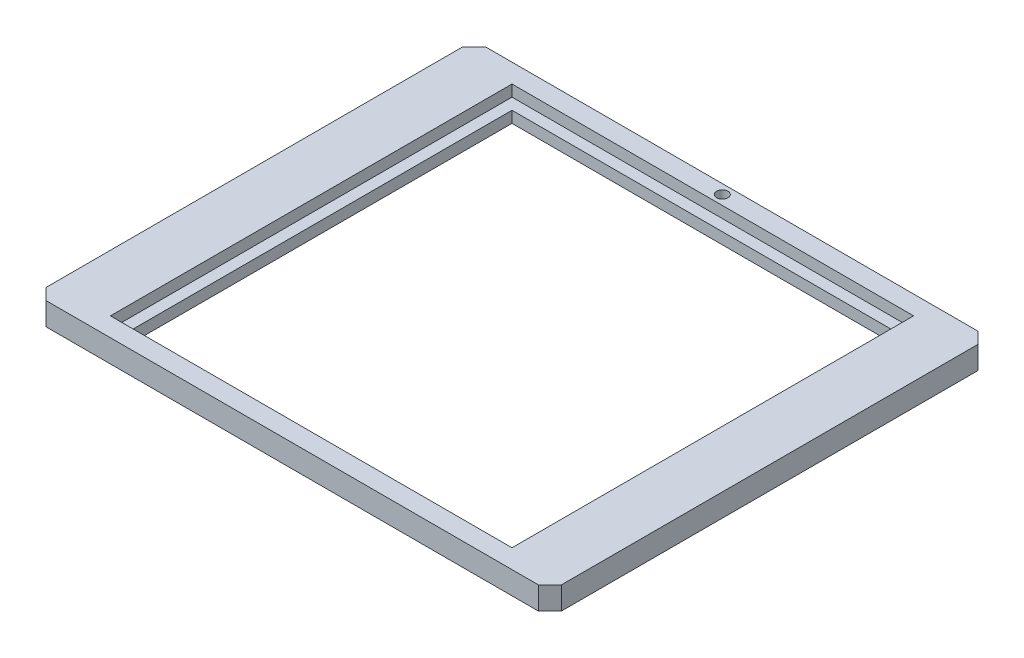
SolidWorks part; units mm, degrees
ref_plane "정면" through (0, 0, 0) normal (0, 0, 1) x (1, 0, 0)
ref_plane "윗면" through (0, 0, 0) normal (0, 1, 0) x (1, 0, 0)
ref_plane "우측면" through (0, 0, 0) normal (1, 0, 0) x (0, 0, -1)
sketch "스케치3" plane through (0, 0, 0) normal (0, 1, 0) x (1, 0, 0)
  line L1 (-68, -58) -> (68, -58)
  line L2 (-68, -58) -> (-68, 58)
  line L3 (-68, 58) -> (68, 58)
  line L4 (68, -58) -> (68, 58)
  line L5 (-68, -58) -> (68, 58) construction
  line L6 (-68, 58) -> (68, -58) construction
  point P0 (0, 0)
  dimension "D1" = 136
  dimension "D2" = 116
extrude "보스-돌출2" add sketch "스케치3" along normal blind 6
sketch "스케치4" plane through (0, 6, 0) normal (0, 1, 0) x (1, 0, 0)
  line L1 (-53, -53) -> (53, -53)
  line L2 (-53, -53) -> (-53, 53)
  line L3 (-53, 53) -> (53, 53)
  line L4 (53, -53) -> (53, 53)
  line L5 (-53, -53) -> (53, 53) construction
  line L6 (-53, 53) -> (53, -53) construction
  point P0 (0, 0)
  dimension "D1" = 106
  dimension "D2" = 106
extrude "컷-돌출1" cut sketch "스케치4" against normal blind 3
sketch "스케치5" plane through (0, 3, 0) normal (0, 1, 0) x (1, 0, 0)
  line L1 (-50, -50) -> (50, -50)
  line L2 (-50, -50) -> (-50, 50)
  line L3 (-50, 50) -> (50, 50)
  line L4 (50, -50) -> (50, 50)
  line L5 (-50, -50) -> (50, 50) construction
  line L6 (-50, 50) -> (50, -50) construction
  point P0 (0, 0)
  dimension "D1" = 100
  dimension "D2" = 100
extrude "컷-돌출2" cut sketch "스케치5" against normal blind 10
chamfer "모따기1" distance 3 angle 45 4 edges at (-68, 3, -58) (68, 3, -58) (68, 3, 58) (-68, 3, 58)
chamfer "모따기2" [suppressed] distance 0.5 angle 45
sketch "스케치6" plane through (0, 6, 0) normal (0, 1, 0) x (1, 0, 0)
  line L0 (65, 58) -> (-65, 58) construction
  circle A0 centre (0, 55.5) radius 1.5
  point P2 (0, 58)
  dimension "D2" = 3
  dimension "D1" = 2.5
extrude "컷-돌출3" cut sketch "스케치6" against normal blind 10
